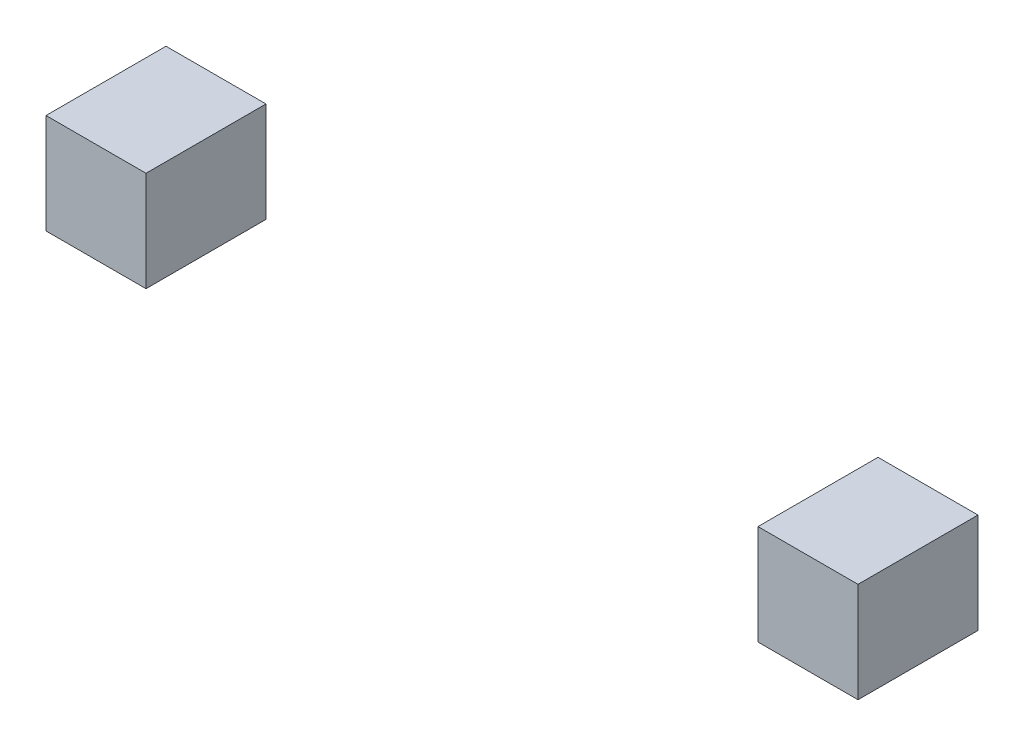
SolidWorks part; units mm, degrees
ref_plane "Front Plane" through (0, 0, 0) normal (0, 0, 1) x (1, 0, 0)
ref_plane "Top Plane" through (0, 0, 0) normal (0, 1, 0) x (1, 0, 0)
ref_plane "Right Plane" through (0, 0, 0) normal (1, 0, 0) x (0, 0, -1)
sketch "Sketch1" plane through (0, 0, 0) normal (0, 0, 1) x (1, 0, 0)
  line L1 (305, 713.79) -> (230, 713.79)
  line L2 (305, 713.79) -> (305, 638.79)
  line L3 (305, 638.79) -> (230, 638.79)
  line L4 (230, 713.79) -> (230, 638.79)
  line L5 (-304, 713.79) -> (-229, 713.79)
  line L6 (-304, 713.79) -> (-304, 638.79)
  line L7 (-304, 638.79) -> (-229, 638.79)
  line L8 (-229, 713.79) -> (-229, 638.79)
  dimension "D1" = 75
  dimension "D2" = 75
  dimension "D3" = 75
  dimension "D4" = 75
extrude "Boss-Extrude1" add sketch "Sketch1" along normal blind 90
